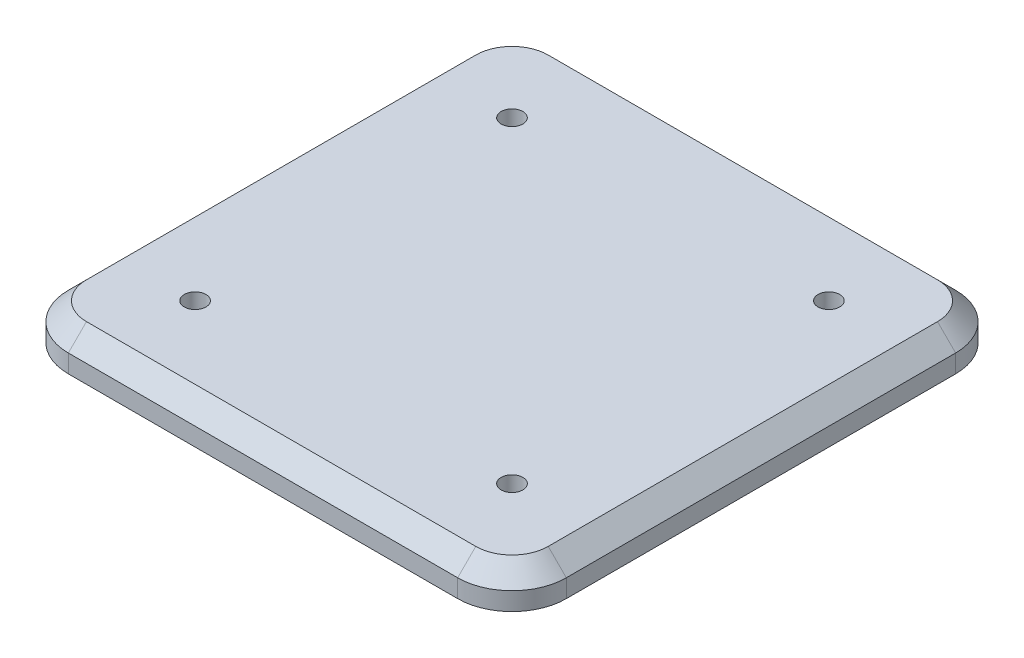
SolidWorks part; units mm, degrees
ref_plane "Front Plane" through (0, 0, 0) normal (0, 0, 1) x (1, 0, 0)
ref_plane "Top Plane" through (0, 0, 0) normal (0, 1, 0) x (1, 0, 0)
ref_plane "Right Plane" through (0, 0, 0) normal (1, 0, 0) x (0, 0, -1)
sketch "Sketch1" plane through (0, 0, 0) normal (0, 1, 0) x (1, 0, 0)
  line L0 (-107.5, 137.5) -> (107.5, 137.5)
  line L1 (137.5, 107.5) -> (137.5, -107.5)
  line L2 (107.5, -137.5) -> (-107.5, -137.5)
  line L3 (-137.5, -107.5) -> (-137.5, 107.5)
  arc A0 (-107.5, -137.5) -> (-137.5, -107.5) centre (-107.5, -107.5) cw
  arc A1 (137.5, -107.5) -> (107.5, -137.5) centre (107.5, -107.5) cw
  arc A2 (107.5, 137.5) -> (137.5, 107.5) centre (107.5, 107.5) cw
  arc A3 (-107.5, 137.5) -> (-137.5, 107.5) centre (-107.5, 107.5) ccw
  point P4 (0, 137.5)
  point P5 (-137.5, 0)
  point P13 (137.5, 137.5)
  point P16 (-137.5, 137.5)
  dimension "D2" = 30
  dimension "D1" = 275
extrude "Boss-Extrude1" add sketch "Sketch1" along normal mid plane 20
chamfer "Chamfer1" distance 10 angle 45 8 edges at (-137.5, 10, 0) (-128.7132, 10, -128.7132) (0, 10, -137.5) (128.7132, 10, -128.7132) (137.5, 10, 0) (128.7132, 10, 128.7132) (0, 10, 137.5) (-128.7132, 10, 128.7132)
sketch "Sketch2" plane through (0, 10, 0) normal (0, 1, 0) x (1, 0, 0)
  line L0 (87.5, 137.5) -> (87.5, -137.5) construction
  line L3 (-107.5, 137.5) -> (107.5, 137.5) construction
  line L4 (107.5, -137.5) -> (-107.5, -137.5) construction
  line L5 (-137.5, -107.5) -> (-137.5, 107.5) construction
  line L6 (-137.5, 87.5) -> (137.5, 87.5) construction
  line L7 (137.5, 107.5) -> (137.5, -107.5) construction
  line L8 (-148.0334, 0) -> (137.5, 0) construction
  line L9 (0, 137.5) -> (0, -137.5) construction
  circle A0 centre (87.5, 87.5) radius 6
  circle A1 centre (-87.5, 87.5) radius 6
  circle A2 centre (87.5, -87.5) radius 6
  circle A3 centre (-87.5, -87.5) radius 6
  dimension "D1" = 50
  dimension "D2" = 50
extrude "Cut-Extrude1" cut sketch "Sketch2" against normal offset from surface (10 mm away) 10 up to face at (0, 10, 0)
sketch "Sketch3" plane through (0, -10, 0) normal (0, -1, 0) x (1, 0, 0)
  line L0 (112.5, 137.5) -> (112.5, -137.5) construction
  line L1 (-107.5, 137.5) -> (107.5, 137.5) construction
  line L2 (107.5, -137.5) -> (-107.5, -137.5) construction
  line L3 (-137.5, 112.5) -> (137.5, 112.5) construction
  line L4 (-137.5, -107.5) -> (-137.5, 107.5) construction
  line L5 (137.5, 107.5) -> (137.5, -107.5) construction
  line L6 (0, 137.5) -> (0, -137.5) construction
  line L7 (-137.5, 0) -> (137.5, 0) construction
  circle A0 centre (112.5, 112.5) radius 6
  circle A1 centre (-112.5, 112.5) radius 6
  circle A2 centre (112.5, -112.5) radius 6
  circle A3 centre (-112.5, -112.5) radius 6
  dimension "D1" = 25
  dimension "D2" = 25
extrude "Cut-Extrude2" cut sketch "Sketch3" against normal offset from surface (10 mm away) 10 up to face at (0, -10, 0)
